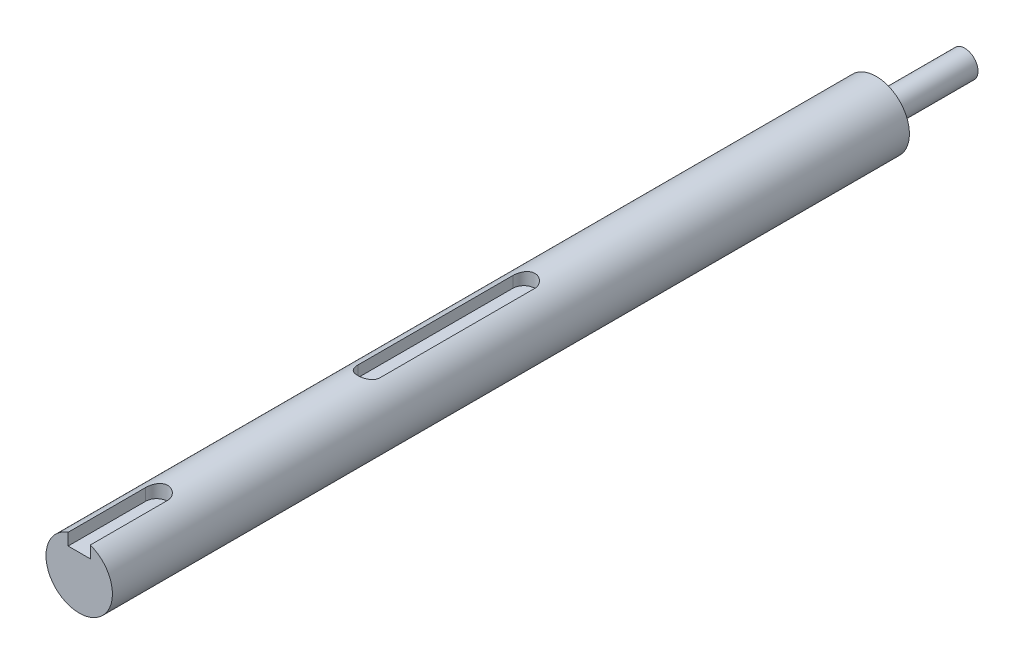
SolidWorks part; units mm, degrees
material "AISI 1045 Steel, cold drawn"
ref_plane "Frontal Plane" through (0, 0, 0) normal (0, 0, 1) x (1, 0, 0)
ref_plane "Horizontal Plane" through (0, 0, 0) normal (0, 1, 0) x (1, 0, 0)
ref_plane "Profile Plane" through (0, 0, 0) normal (1, 0, 0) x (0, 0, -1)
sketch "Sketch1" plane through (0, 0, 0) normal (0, 0, 1) x (1, 0, 0)
  circle A0 centre (0, 0) radius 7.5
  dimension "D1" = 15
extrude "Boss-Extrude1" add sketch "Sketch1" along normal blind 200
sketch "Sketch2" plane through (0, 0, 0) normal (0, 0, -1) x (-1, 0, 0)
  circle A0 centre (0, 0) radius 3
  circle A1 centre (0, 0) radius 7.5
  dimension "D1" = 6
  dimension "D2" = 4.5
extrude "Cut-Extrude1" cut sketch "Sketch2" against normal blind 20
ref_plane "Plane1" [suppressed] through (0, 7.5, 0) normal (0, 1, 0) x (1, 0, 0)
sketch "Sketch3" [suppressed] plane through (0, 7.5, 0) normal (0, 1, 0) x (1, 0, 0)
  line L0 (0, -99.5781) -> (0, -134.5781) construction
  line L1 (2.5, -99.5781) -> (2.5, -134.5781)
  line L2 (-2.5, -99.5781) -> (-2.5, -134.5781)
  line L3 (-7.5, -200) -> (7.5, -200) construction
  arc A0 (2.5, -99.5781) -> (-2.5, -99.5781) centre (0, -99.5781) ccw
  arc A1 (-2.5, -134.5781) -> (2.5, -134.5781) centre (0, -134.5781) ccw
  point P2 (0, -117.0781)
  dimension "D3" = 35
  dimension "D1" = 82.9219
  dimension "D2" = 5
extrude "Cut-Extrude2" [suppressed] cut sketch "Sketch3" against normal blind 2.5
sketch "Sketch4" plane through (0, 0, 200) normal (0, 0, 1) x (1, 0, 0)
  line L0 (-2.5, 7.0711) -> (2.5, 7.0711) construction
  arc A0 (2.5, 7.0711) -> (-2.5, 7.0711) centre (0, 0) cw construction
  circle A1 centre (0, 0) radius 7.5 construction
  dimension "D1" = 5
ref_plane "Plane2" through (0, 7.0711, 0) normal (0, 1, 0) x (1, 0, 0)
sketch "Sketch5" plane through (0, 7.0711, 0) normal (0, 1, 0) x (1, 0, 0)
  line L0 (0, -99.5781) -> (0, -134.5781) construction
  line L1 (2.5, -99.5781) -> (2.5, -134.5781)
  line L2 (-2.5, -99.5781) -> (-2.5, -134.5781)
  line L3 (-7.5, -200) -> (7.5, -200) construction
  arc A0 (2.5, -99.5781) -> (-2.5, -99.5781) centre (0, -99.5781) ccw
  arc A1 (-2.5, -134.5781) -> (2.5, -134.5781) centre (0, -134.5781) ccw
  point P2 (0, -117.0781)
  dimension "D1" = 5
  dimension "D2" = 35
  dimension "D3" = 82.9219
extrude "Cut-Extrude3" cut sketch "Sketch5" against normal blind 12.5 from offset 10
sketch "Sketch6" plane through (0, 7.0711, 0) normal (0, 1, 0) x (1, 0, 0)
  line L0 (0, -200) -> (0, -182.5) construction
  line L1 (-7.5, -200) -> (7.5, -200) construction
  line L2 (-2.5, -200) -> (-2.5, -182.5)
  line L3 (2.5, -200) -> (2.5, -182.5)
  arc A0 (-2.5, -200) -> (2.5, -200) centre (0, -200) ccw
  arc A1 (2.5, -182.5) -> (-2.5, -182.5) centre (0, -182.5) ccw
  point P5 (0, -191.25)
  dimension "D1" = 5
  dimension "D2" = 17.5
extrude "Cut-Extrude4" cut sketch "Sketch6" against normal blind 12.7 from offset 10
equation "\"WallThickness\"= 0.5cm"
equation "\"BottomPlateX\"= 3ft"
equation "\"BottomPlateZ\"= 2ft"
equation "\"BottomPlateHoleD\"=((\"ArmPlateX\")^2+(\"ArmPlateDepth\")^2)^.5+ 10mm"
equation "\"ActuatorPinD\"= 6.35mm"
equation "\"ActuatorPinL\"= 15cm"
equation "\"Box-X\"= 40cm"
equation "\"Box-Z\"= 20cm"
equation "\"Box-Y\"= 30cm"
equation "\"ArmPlateThickness\"= .125in"
equation "\"ArmPlateX\"= 18in"
equation "\"ArmPlateDepth\"= 7.1875in"
equation "\"DCMotor1D\"= 65mm"
equation "\"DCMotor1L\"= 215mm"
equation "\"DCMotor1ShaftL\"= 30mm"
equation "\"DCMotor2X\"= 68mm"
equation "\"DCMotor2D\"= 65mm"
equation "\"DCMotor2L\"= 208mm"
equation "\"DCMotor2ShaftL\"= 39mm"
equation "\"DCMotor2ShaftD\"= 15mm"
equation "\"BenchDepth\"= 5cm"
equation "\"BenchH\"= 10cm"
equation "\"BenchL\"= 15cm"
equation "\"PillowBlockW\"= 5cm"
equation "\"PillowBlockCenterH\"= \"DCMotor2X\"/2"
equation "\"EncoderRadius\"= 19mm"
equation "\"EncoderShaftL\"= 15mm"
equation "\"EncoderL\"= 33mm"
equation "\"EncoderHousingThickness\"= 7.5mm"
equation "\"TurntableID\"= 70mm"
equation "\"TurntableInner2*t\" = (\"TurntableOD\"-\"TurntableID\")*.25 - 1mm"
equation "\"TurntableInnerHoleRadius\"= \"TurntableID\"*.5 + \"TurntableInner2*t\"*.5"
equation "\"TurntableOD\"= 120mm"
equation "\"TurntableOuterHoleRadius\" = \"TurntableOD\"*.5 - ((\"TurntableOD\"-\"TurntableID\")*.25-.5mm)*.5"
equation "\"2525Height\" = 30cm"
equation "\"D1@Sketch1\"=\"DCMotor2ShaftD\""
equation "\"D1@Boss-Extrude1\"=\"ActuatorPinL\"*.25+2mm"
